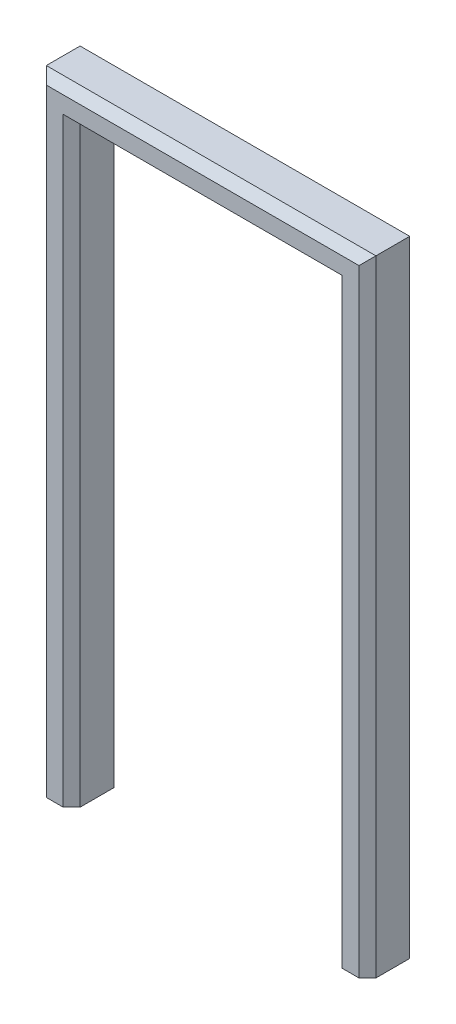
SolidWorks part; units mm, degrees
ref_plane "Front Plane" through (0, 0, 0) normal (0, 0, 1) x (1, 0, 0)
ref_plane "Top Plane" through (0, 0, 0) normal (0, 1, 0) x (1, 0, 0)
ref_plane "Right Plane" through (0, 0, 0) normal (1, 0, 0) x (0, 0, -1)
sketch "Sketch1" plane through (0, 0, 0) normal (0, 1, 0) x (1, 0, 0)
  line L0 (-35, 0) -> (35, 0) construction
  line L1 (-39, -6) -> (-31, -6)
  line L2 (-39, -6) -> (-39, 6)
  line L3 (-39, 6) -> (-31, 6)
  line L4 (-31, -6) -> (-31, 6)
  line L5 (-39, -6) -> (-31, 6) construction
  line L6 (-39, 6) -> (-31, -6) construction
  line L7 (31, -6) -> (39, -6)
  line L8 (31, -6) -> (31, 6)
  line L9 (31, 6) -> (39, 6)
  line L10 (39, -6) -> (39, 6)
  line L11 (31, -6) -> (39, 6) construction
  line L12 (31, 6) -> (39, -6) construction
  point P0 (-35, 0)
  point P5 (35, 0)
  point P12 (0, 0)
  dimension "D1" = 12
  dimension "D2" = 8
  dimension "D3" = 70
extrude "Boss-Extrude1" add sketch "Sketch1" along normal blind 140
sketch "Sketch2" plane through (0, 140, 0) normal (0, 1, 0) x (1, 0, 0)
  line L1 (-39, 6) -> (39, 6)
  line L2 (-39, 6) -> (-39, -6)
  line L3 (-39, -6) -> (39, -6)
  line L4 (39, 6) -> (39, -6)
extrude "Boss-Extrude2" add sketch "Sketch2" along normal blind 8
chamfer "Chamfer1" distance 2 angle 45 12 edges at (39, 74, -6) (0, 148, -6) (-39, 74, -6) (31, 70, -6) (0, 140, -6) (-31, 70, -6) (-31, 70, 6) (0, 140, 6) (31, 70, 6) (39, 74, 6) (0, 148, 6) (-39, 74, 6)
